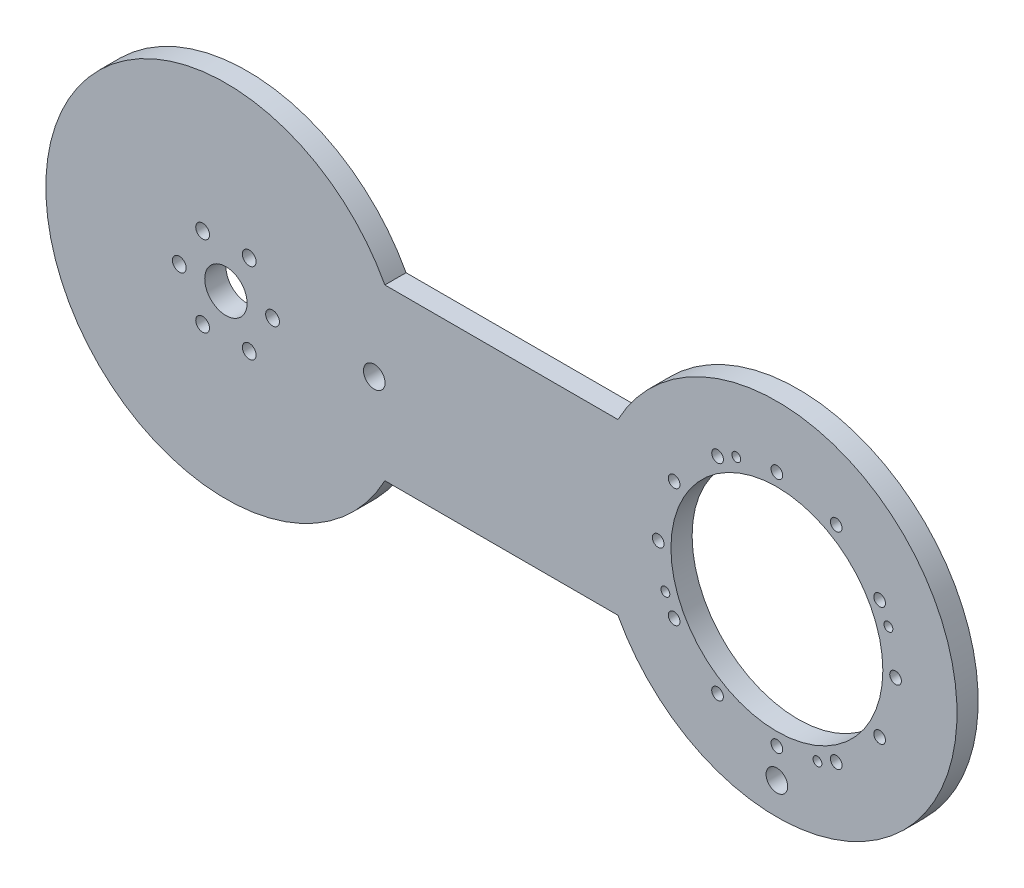
SolidWorks part; units mm, degrees
material "6061-T6 (SS)"
ref_plane "前视基准面" through (0, 0, 0) normal (0, 0, 1) x (1, 0, 0)
ref_plane "上视基准面" through (0, 0, 0) normal (0, 1, 0) x (1, 0, 0)
ref_plane "右视基准面" through (0, 0, 0) normal (1, 0, 0) x (0, 0, -1)
other "Configuration Table"
sketch "草图1" plane through (0, 0, 0) normal (0, 0, 1) x (1, 0, 0)
  circle A0 centre (0, 0) radius 85
extrude "凸台-拉伸1" add sketch "草图1" along normal blind 10
sketch "草图2" plane through (0, 0, 0) normal (0, 0, 1) x (1, 0, 0)
  line L0 (0, -40) -> (260, -40)
  line L1 (260, -40) -> (260, 40)
  line L2 (260, 40) -> (0, 40)
  line L3 (0, 40) -> (0, -40)
extrude "凸台-拉伸2" add sketch "草图2" along normal blind 10
sketch "草图3" plane through (0, 0, 0) normal (0, 0, 1) x (1, 0, 0)
  circle A0 centre (260, 0) radius 85
extrude "凸台-拉伸3" add sketch "草图3" along normal blind 10
sketch "草图4" plane through (0, 0, 0) normal (0, 0, -1) x (-1, 0, 0)
  circle A0 centre (0, 0) radius 10
  circle A1 centre (-22, 0) radius 3.25
  circle A2 centre (-11, 19.0526) radius 3.25
  circle A3 centre (11, 19.0526) radius 3.25
  circle A4 centre (22, 0) radius 3.25
  circle A5 centre (11, -19.0526) radius 3.25
  circle A6 centre (-11, -19.0526) radius 3.25
  circle A7 centre (-260, 0) radius 50
  circle A8 centre (-316, 0) radius 2.75
  circle A9 centre (-308.4974, 28) radius 2.75
  circle A10 centre (-288, 48.4974) radius 2.75
  circle A11 centre (-260, 56) radius 2.75
  circle A12 centre (-232, 48.4974) radius 2.75
  circle A13 centre (-211.5026, 28) radius 2.75
  circle A14 centre (-204, 0) radius 2.75
  circle A15 centre (-211.5026, -28) radius 2.75
  circle A16 centre (-232, -48.4974) radius 2.75
  circle A17 centre (-260, -56) radius 2.75
  circle A18 centre (-288, -48.4974) radius 2.75
  circle A19 centre (-308.4974, -28) radius 2.75
  circle A20 centre (-312.6228, 19.1531) radius 2.1
  circle A21 centre (-240.8469, 52.6228) radius 2.1
  circle A22 centre (-207.3772, -19.1531) radius 2.1
  circle A23 centre (-279.1531, -52.6228) radius 2.1
  circle A24 centre (-70, 0) radius 5.1
  circle A25 centre (-260, -70) radius 5.1
extrude "切除-拉伸1" cut sketch "草图4" against normal blind 11
